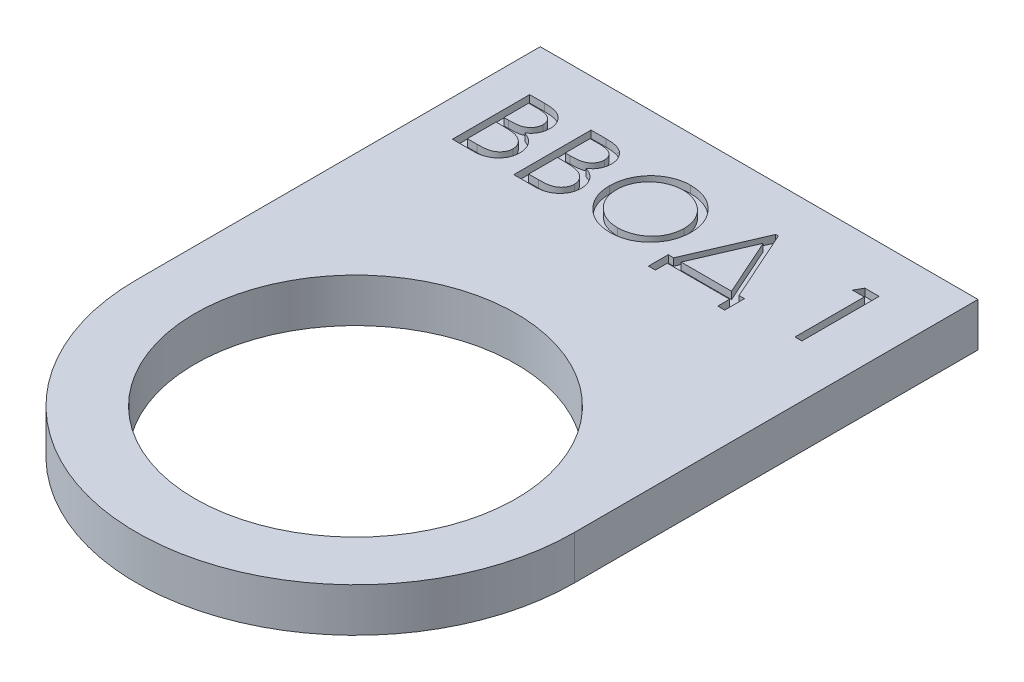
SolidWorks part; units mm, degrees
ref_plane "Front Plane" through (0, 0, 0) normal (0, 0, 1) x (1, 0, 0)
ref_plane "Top Plane" through (0, 0, 0) normal (0, 1, 0) x (1, 0, 0)
ref_plane "Right Plane" through (0, 0, 0) normal (1, 0, 0) x (0, 0, -1)
sketch "Sketch1" plane through (0, 0, 0) normal (0, 1, 0) x (1, 0, 0)
  line L0 (-19.7525, -10.1623) -> (19.1814, -10.1623) construction
  line L1 (15, 17.5) -> (-15, 17.5)
  line L2 (15, 17.5) -> (15, -10.1623)
  line L4 (-15, 17.5) -> (-15, -10.1623)
  line L5 (0, 15.6015) -> (0, -29.3739) construction
  line L6 (-18.6113, 0) -> (19.987, 0) construction
  arc A0 (-15, -10.1623) -> (15, -10.1623) centre (0, -10.1623) ccw
  circle A1 centre (0, -10.1623) radius 11
  point P0 (0, 0)
  dimension "D1" = 22
  dimension "D3" = 15
  dimension "D2" = 17.5
extrude "Boss-Extrude1" add sketch "Sketch1" along normal mid plane 3
sketch "Sketch2" plane through (0, 1.5, 0) normal (0, 1, 0) x (1, 0, 0)
  line L0 (15, 9) -> (-15, 9) construction
  line L1 (-15, 17.5) -> (-15, -10.1623) construction
  line L2 (15, 17.5) -> (-15, 17.5) construction
  line L3 (15, -10.1623) -> (15, 17.5) construction
  text T0 "ВВОД 1" font "Century Gothic" height in points 20
  dimension "D1" = 8.5
extrude "Cut-Extrude1" cut sketch "Sketch2" against normal blind 0.5
